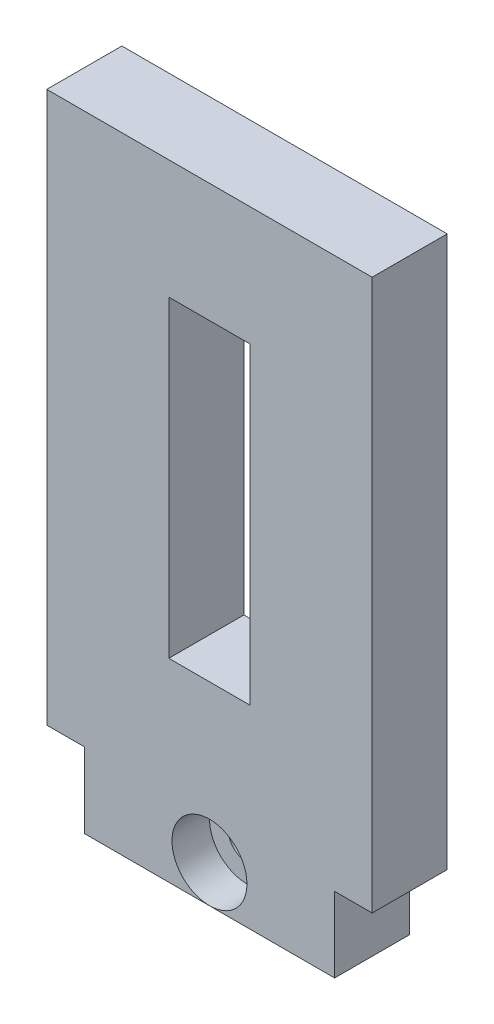
SolidWorks part; units mm, degrees
ref_plane "Plan de face" through (0, 0, 0) normal (0, 0, 1) x (1, 0, 0)
ref_plane "Plan de dessus" through (0, 0, 0) normal (0, 1, 0) x (1, 0, 0)
ref_plane "Plan de droite" through (0, 0, 0) normal (1, 0, 0) x (0, 0, -1)
sketch "Esquisse1" plane through (0, 0, 0) normal (0, 0, 1) x (1, 0, 0)
  line L1 (0, 0) -> (44, 0)
  line L2 (0, 0) -> (0, 44)
  line L3 (0, 44) -> (44, 44)
  line L4 (44, 0) -> (44, 44)
  dimension "D1" = 44
  dimension "D2" = 44
extrude "Boss.-Extru.1" add sketch "Esquisse1" along normal blind 6
sketch "Esquisse2" plane through (0, 0, 6) normal (0, 0, 1) x (1, 0, 0)
  line L0 (0, 0) -> (44, 0) construction
  line L1 (12, 0) -> (32, 0)
  line L2 (12, 0) -> (12, -6)
  line L3 (12, -6) -> (32, -6)
  line L4 (32, 0) -> (32, -6)
  line L5 (44, 0) -> (44, 44) construction
  dimension "D1" = 20
  dimension "D2" = 6
  dimension "D3" = 12
extrude "Boss.-Extru.3" add sketch "Esquisse2" against normal blind 6
sketch "Esquisse3" plane through (0, 0, 6) normal (0, 0, 1) x (1, 0, 0)
  line L0 (0, 44) -> (0, 0) construction
  line L1 (18.75, 34.5) -> (25.25, 34.5)
  line L2 (18.75, 34.5) -> (18.75, 9.5)
  line L3 (18.75, 9.5) -> (25.25, 9.5)
  line L4 (25.25, 34.5) -> (25.25, 9.5)
  line L5 (44, 0) -> (44, 44) construction
  line L6 (0, 0) -> (12, 0) construction
  line L7 (44, 44) -> (0, 44) construction
  dimension "D1" = 6.5
  dimension "D2" = 18.75
  dimension "D3" = 18.75
  dimension "D4" = 9.5
  dimension "D5" = 9.5
extrude "Enlèv. mat.-Extru.1" cut sketch "Esquisse3" against normal blind 6
sketch "Esquisse4" plane through (0, 0, 6) normal (0, 0, 1) x (1, 0, 0)
  line L0 (0, 0) -> (12, 0) construction
  line L1 (0, 44) -> (9, 44)
  line L2 (0, 44) -> (0, 0)
  line L3 (0, 0) -> (9, 0)
  line L4 (9, 44) -> (9, 0)
  line L5 (32, 0) -> (44, 0) construction
  line L6 (44, 44) -> (35, 44)
  line L7 (44, 44) -> (44, 0)
  line L8 (44, 0) -> (35, 0)
  line L9 (35, 44) -> (35, 0)
  dimension "D1" = 9
  dimension "D2" = 9
extrude "Enlèv. mat.-Extru.2" cut sketch "Esquisse4" against normal blind 6
sketch "Esquisse5" plane through (0, 0, 6) normal (0, 0, 1) x (1, 0, 0)
  line L0 (12, 0) -> (12, -6) construction
  line L1 (12, -6) -> (32, -6) construction
  circle A0 centre (22, -3) radius 1.5
  point P2 (12, -3)
  dimension "D1" = 3
  dimension "D2" = 10
  dimension "D3" = 3
extrude "Enlèv. mat.-Extru.3" cut sketch "Esquisse5" against normal blind 6
sketch "Esquisse6" plane through (0, 0, 6) normal (0, 0, 1) x (1, 0, 0)
  circle A0 centre (22, -3) radius 2.995
  dimension "D1" = 5.99
extrude "Enlèv. mat.-Extru.4" cut sketch "Esquisse6" against normal blind 3
